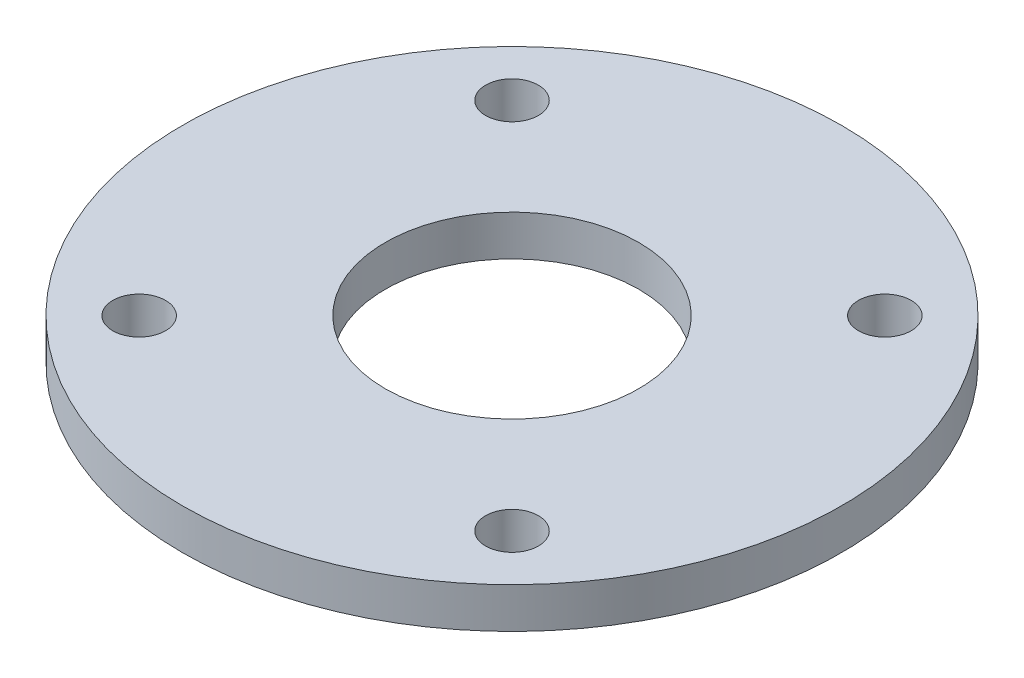
SolidWorks part; units mm, degrees
ref_plane "Front Plane" through (0, 0, 0) normal (0, 0, 1) x (1, 0, 0)
ref_plane "Top Plane" through (0, 0, 0) normal (0, 1, 0) x (1, 0, 0)
ref_plane "Right Plane" through (0, 0, 0) normal (1, 0, 0) x (0, 0, -1)
sketch "Sketch1" plane through (0, 0, 0) normal (0, 1, 0) x (1, 0, 0)
  line L1 (18.3848, -18.3848) -> (-18.3848, -18.3848) construction
  line L2 (18.3848, -18.3848) -> (18.3848, 18.3848) construction
  line L3 (18.3848, 18.3848) -> (-18.3848, 18.3848) construction
  line L4 (-18.3848, -18.3848) -> (-18.3848, 18.3848) construction
  line L5 (18.3848, -18.3848) -> (-18.3848, 18.3848) construction
  line L6 (18.3848, 18.3848) -> (-18.3848, -18.3848) construction
  circle A0 centre (0, 0) radius 12.5
  circle A1 centre (0, 0) radius 20 construction
  circle A2 centre (18.3848, -18.3848) radius 2.6
  circle A3 centre (-18.3848, -18.3848) radius 2.6
  circle A4 centre (-18.3848, 18.3848) radius 2.6
  circle A5 centre (18.3848, 18.3848) radius 2.6
  circle A6 centre (0, 0) radius 32.5
  circle A7 centre (0, 0) radius 26 construction
  dimension "D1" = 25
  dimension "D2" = 40
  dimension "D4" = 5.2
  dimension "D5" = 65
  dimension "D3" = 52
extrude "Boss-Extrude1" add sketch "Sketch1" along normal blind 4
